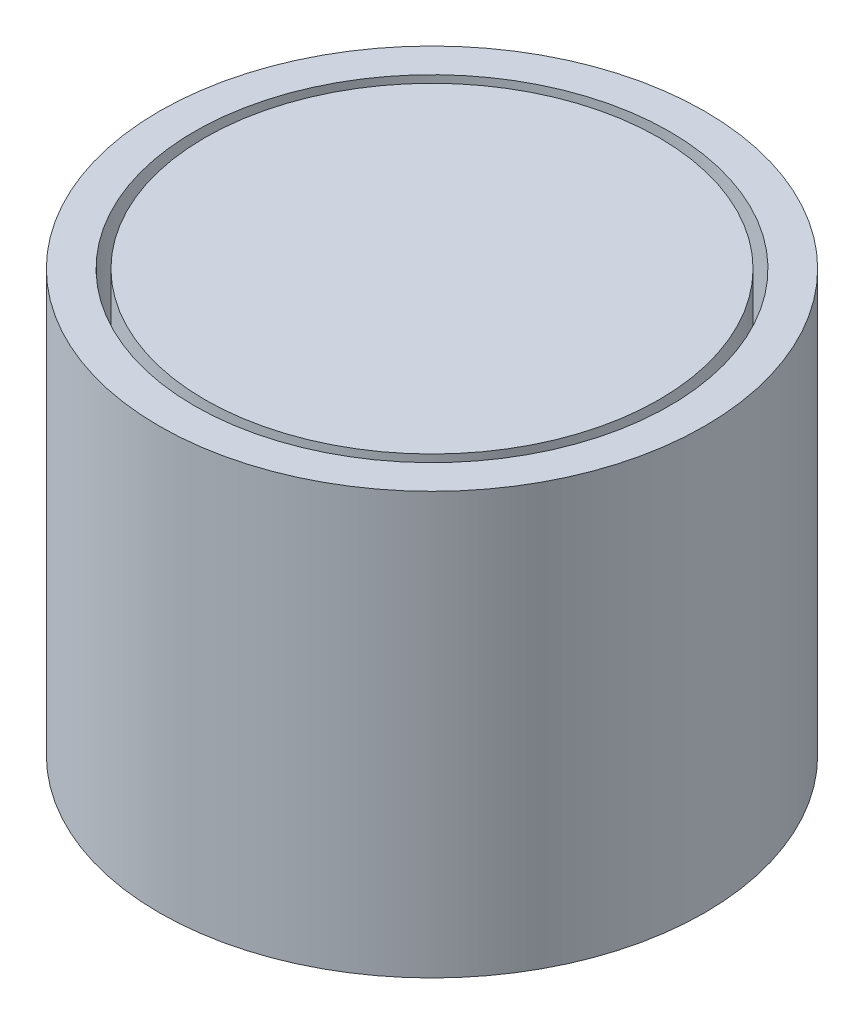
SolidWorks part; units mm, degrees
ref_plane "前视基准面" through (0, 0, 0) normal (0, 0, 1) x (1, 0, 0)
ref_plane "上视基准面" through (0, 0, 0) normal (0, 1, 0) x (1, 0, 0)
ref_plane "右视基准面" through (0, 0, 0) normal (1, 0, 0) x (0, 0, -1)
sketch "草图1" plane through (0, 0, 0) normal (0, 1, 0) x (1, 0, 0)
  circle A0 centre (0, 0) radius 11
  dimension "D1" = 22
extrude "凸台-拉伸1" add sketch "草图1" along normal blind 17
sketch "草图2" plane through (0, 17, 0) normal (0, 1, 0) x (1, 0, 0)
  circle A0 centre (0, 0) radius 9.5829
extrude "切除-拉伸1" cut sketch "草图2" against normal blind 16
sketch "草图3" plane through (0, 1, 0) normal (0, 1, 0) x (1, 0, 0)
  circle A0 centre (0, 0) radius 9.1575
extrude "凸台-拉伸2" add sketch "草图3" along normal blind 16
